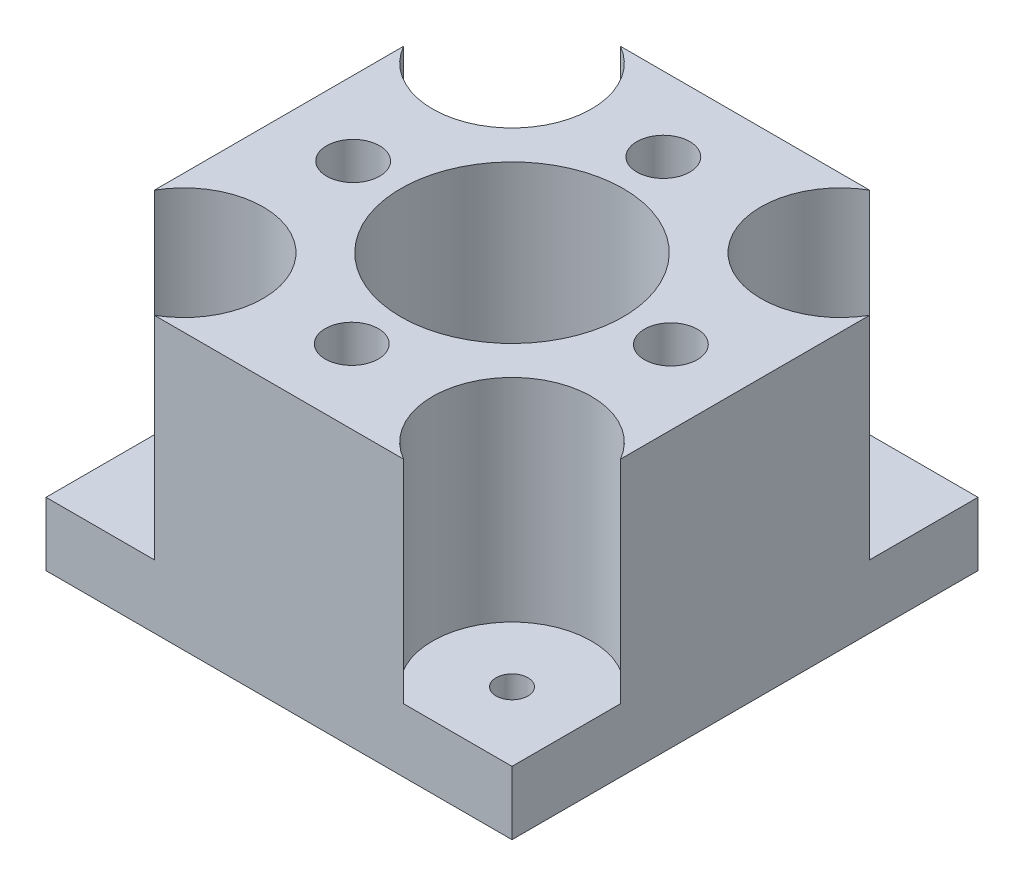
SolidWorks part; units mm, degrees
ref_plane "Front Plane" through (0, 0, 0) normal (0, 0, 1) x (1, 0, 0)
ref_plane "Top Plane" through (0, 0, 0) normal (0, 1, 0) x (1, 0, 0)
ref_plane "Right Plane" through (0, 0, 0) normal (1, 0, 0) x (0, 0, -1)
sketch "Sketch1" plane through (0, 0, 0) normal (0, 1, 0) x (1, 0, 0)
  line L1 (-22, -22) -> (22, -22)
  line L2 (-22, -22) -> (-22, 22)
  line L3 (-22, 22) -> (22, 22)
  line L4 (22, -22) -> (22, 22)
  line L5 (-22, -22) -> (22, 22) construction
  line L6 (-22, 22) -> (22, -22) construction
  circle A0 centre (-15.5, 15.5) radius 1.5
  circle A1 centre (15.5, 15.5) radius 1.5
  circle A2 centre (-15.5, -15.5) radius 1.5
  circle A3 centre (15.5, -15.5) radius 1.5
  point P0 (0, 0)
  dimension "D4" = 3
  dimension "D5" = 31
  dimension "D6" = 3
  dimension "D7" = 3
  dimension "D9" = 3
  dimension "D1" = 44
  dimension "D2" = 44
  dimension "D3" = 15.5
  dimension "D8" = 15.5
extrude "Boss-Extrude1" add sketch "Sketch1" along normal blind 3
sketch "Sketch2" plane through (0, 3, 0) normal (0, 1, 0) x (1, 0, 0)
  line L1 (-18, -18) -> (18, -18)
  line L2 (-18, -18) -> (-18, 18)
  line L3 (-18, 18) -> (18, 18)
  line L4 (22, -22) -> (22, 22)
  line L5 (22, 22) -> (-22, 22)
  line L6 (-22, 22) -> (-22, -22)
  line L7 (-22, -22) -> (22, -22)
  line L8 (22, -22) -> (22, 22)
  line L9 (22, 22) -> (-22, 22)
  line L10 (-22, 22) -> (-22, -22)
  line L11 (-22, -22) -> (22, -22)
  line L12 (18, -18) -> (18, 18)
  line L13 (-18, -18) -> (18, 18) construction
  line L14 (-18, 18) -> (18, -18) construction
  point P2 (0, 0)
  dimension "D2" = 4
  dimension "D3" = 4
  dimension "D1" = 0
extrude "Boss-Extrude2" add sketch "Sketch2" along normal blind 20
sketch "Sketch3" plane through (0, 3, 0) normal (0, 1, 0) x (1, 0, 0)
  circle A0 centre (0, 0) radius 10.5
  dimension "D1" = 21
extrude "Cut-Extrude1" cut sketch "Sketch3" against normal blind 20
sketch "Sketch4" plane through (0, 23, 0) normal (0, 1, 0) x (1, 0, 0)
  line L4 (-22, -22) -> (22, -22)
  line L5 (22, -22) -> (22, 22)
  line L6 (22, 22) -> (-22, 22)
  line L7 (-22, 22) -> (-22, -22)
  line L8 (-22, -22) -> (22, -22)
  line L9 (22, -22) -> (22, 22)
  line L10 (22, 22) -> (-22, 22)
  line L11 (-22, 22) -> (-22, -22)
  dimension "D1" = 0
extrude "Boss-Extrude3" add sketch "Sketch4" along normal blind 3
sketch "Sketch5" plane through (0, 26, 0) normal (0, 1, 0) x (1, 0, 0)
  line L0 (-22, 22) -> (-22, 19.2417)
  line L1 (-22, 22) -> (-22, -22) construction
  line L2 (-22, 22) -> (-19.2417, 22)
  line L3 (22, 22) -> (19.2417, 22)
  line L4 (22, 22) -> (22, 19.2417)
  line L5 (22, -22) -> (22, -19.2417)
  line L6 (22, -22) -> (19.2417, -22)
  line L7 (-22, -22) -> (22, -22) construction
  line L12 (-22, -22) -> (-22, -19.2417)
  line L13 (-22, -22) -> (-19.2417, -22)
  circle A0 centre (0, 0) radius 10.5 construction
  circle A1 centre (0, 0) radius 10.5
  arc A10 (-22, 19.2417) -> (-19.2417, 22) centre (-15.5, 15.5) ccw
  arc A11 (-19.2417, -22) -> (-22, -19.2417) centre (-15.5, -15.5) ccw
  arc A12 (22, -19.2417) -> (19.2417, -22) centre (15.5, -15.5) ccw
  arc A13 (19.2417, 22) -> (22, 19.2417) centre (15.5, 15.5) ccw
  dimension "D1" = 15
  dimension "D2" = 15
  dimension "D3" = 15
  dimension "D4" = 15
extrude "Cut-Extrude2" cut sketch "Sketch5" against normal blind 20
sketch "Sketch6" plane through (0, 23, 0) normal (0, -1, 0) x (1, 0, 0)
  line L4 (8.4289, 18) -> (-8.4289, 18)
  line L5 (-18, 8.4289) -> (-18, -8.4289)
  line L6 (-8.4289, -18) -> (8.4289, -18)
  line L7 (18, -8.4289) -> (18, 8.4289)
  line L8 (8.4289, 18) -> (-8.4289, 18)
  line L9 (-18, 8.4289) -> (-18, -8.4289)
  line L10 (-8.4289, -18) -> (8.4289, -18)
  line L11 (18, -8.4289) -> (18, 8.4289)
  circle A0 centre (0, 0) radius 10.5 construction
  circle A1 centre (0, 0) radius 10.5
  arc A4 (-18, 8.4289) -> (-8.4289, 18) centre (-15.5, 15.5) ccw
  arc A5 (-8.4289, -18) -> (-18, -8.4289) centre (-15.5, -15.5) ccw
  arc A6 (18, -8.4289) -> (8.4289, -18) centre (15.5, -15.5) ccw
  arc A7 (8.4289, 18) -> (18, 8.4289) centre (15.5, 15.5) ccw
  arc A8 (-18, 8.4289) -> (-8.4289, 18) centre (-15.5, 15.5) ccw
  arc A9 (-8.4289, -18) -> (-18, -8.4289) centre (-15.5, -15.5) ccw
  arc A10 (18, -8.4289) -> (8.4289, -18) centre (15.5, -15.5) ccw
  arc A11 (8.4289, 18) -> (18, 8.4289) centre (15.5, 15.5) ccw
  dimension "D1" = 0
extrude "Boss-Extrude4" add sketch "Sketch6" along normal blind 23
sketch "Sketch7" plane through (0, 26, 0) normal (0, 1, 0) x (1, 0, 0)
  circle A0 centre (15, 0) radius 2.5
  circle A1 centre (-15, 0) radius 2.5
  circle A2 centre (-0.6954, 14.9839) radius 2.5
  circle A3 centre (-0.1153, -15.0161) radius 2.5
  point P8 (0, 0)
  dimension "D1" = 5
  dimension "D2" = 5
  dimension "D3" = 5
  dimension "D4" = 5
  dimension "D5" = 30
  dimension "D6" = 30
  dimension "D7" = 15
  dimension "D8" = 15
extrude "Cut-Extrude3" cut sketch "Sketch7" against normal blind 33
sketch "Sketch8" plane through (0, 3, 0) normal (0, 1, 0) x (1, 0, 0)
  line L2 (8.4289, -18) -> (18, -18)
  line L3 (18, -18) -> (18, -8.4289)
  line L4 (8.4289, -18) -> (18, -18)
  line L5 (18, -18) -> (18, -8.4289)
  line L6 (18, 8.4289) -> (18, 18)
  line L7 (18, 18) -> (8.4289, 18)
  line L8 (18, 8.4289) -> (18, 18)
  line L9 (18, 18) -> (8.4289, 18)
  line L10 (-8.4289, 18) -> (-18, 18)
  line L11 (-18, 18) -> (-18, 8.4289)
  line L12 (-8.4289, 18) -> (-18, 18)
  line L13 (-18, 18) -> (-18, 8.4289)
  line L14 (-18, -8.4289) -> (-18, -18)
  line L15 (-18, -18) -> (-8.4289, -18)
  line L16 (-18, -8.4289) -> (-18, -18)
  line L17 (-18, -18) -> (-8.4289, -18)
  circle A0 centre (15.5, -15.5) radius 1.5 construction
  arc A1 (18, -8.4289) -> (8.4289, -18) centre (15.5, -15.5) ccw
  arc A2 (18, -8.4289) -> (8.4289, -18) centre (15.5, -15.5) ccw
  circle A3 centre (15.5, -15.5) radius 1.5
  circle A4 centre (15.5, 15.5) radius 1.5 construction
  arc A5 (8.4289, 18) -> (18, 8.4289) centre (15.5, 15.5) ccw
  arc A6 (8.4289, 18) -> (18, 8.4289) centre (15.5, 15.5) ccw
  circle A7 centre (15.5, 15.5) radius 1.5
  circle A8 centre (-15.5, 15.5) radius 1.5 construction
  arc A9 (-18, 8.4289) -> (-8.4289, 18) centre (-15.5, 15.5) ccw
  arc A10 (-18, 8.4289) -> (-8.4289, 18) centre (-15.5, 15.5) ccw
  arc A11 (-8.4289, -18) -> (-18, -8.4289) centre (-15.5, -15.5) ccw
  arc A12 (-8.4289, -18) -> (-18, -8.4289) centre (-15.5, -15.5) ccw
  circle A13 centre (-15.5, 15.5) radius 1.5
  circle A14 centre (-15.5, -15.5) radius 1.5 construction
  circle A15 centre (-15.5, -15.5) radius 1.5
  dimension "D1" = 0
  dimension "D2" = 0
  dimension "D3" = 0
  dimension "D4" = 0
extrude "Boss-Extrude5" add sketch "Sketch8" along normal up to surface (3 mm away) up to face at (-16.6879, 6, -16.6879)
